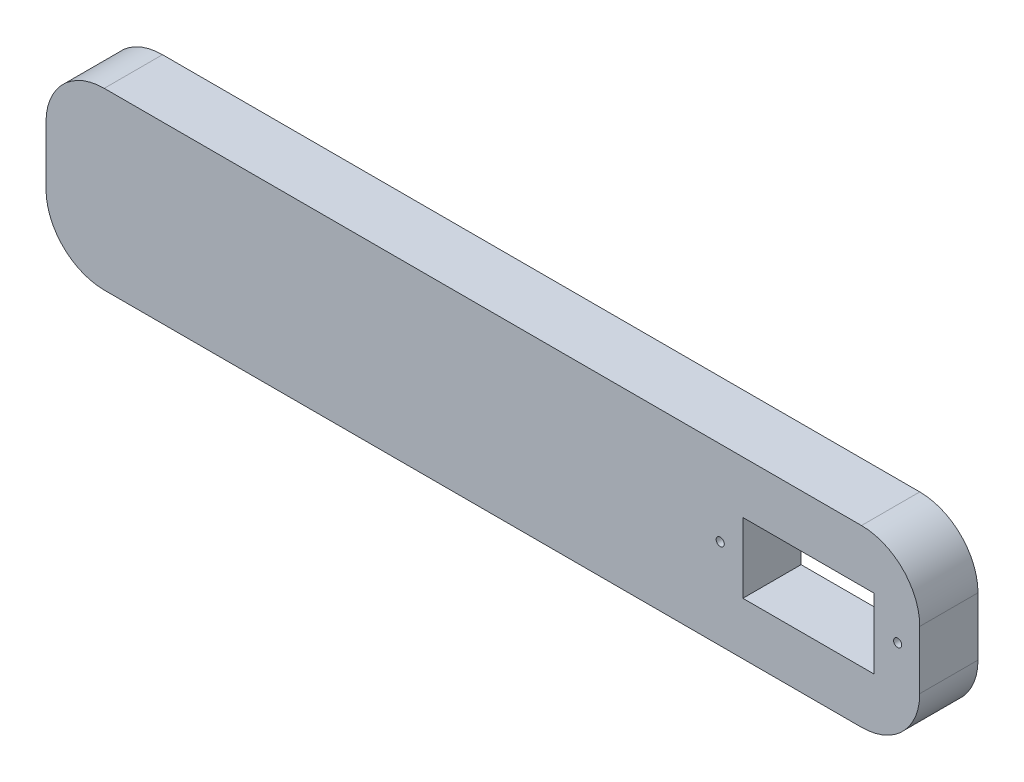
SolidWorks part; units mm, degrees
ref_plane "Front Plane" through (0, 0, 0) normal (0, 0, 1) x (1, 0, 0)
ref_plane "Top Plane" through (0, 0, 0) normal (0, 1, 0) x (1, 0, 0)
ref_plane "Right Plane" through (0, 0, 0) normal (1, 0, 0) x (0, 0, -1)
sketch "Sketch1" plane through (0, 0, 0) normal (0, 0, 1) x (1, 0, 0)
  line L1 (10, 0) -> (140, 0)
  line L2 (0, 10) -> (0, 20)
  line L3 (10, 30) -> (140, 30)
  line L4 (150, 10) -> (150, 20)
  arc A0 (0, 20) -> (10, 30) centre (10, 20) cw
  arc A1 (10, 0) -> (0, 10) centre (10, 10) cw
  arc A2 (140, 0) -> (150, 10) centre (140, 10) ccw
  arc A3 (140, 30) -> (150, 20) centre (140, 20) cw
  point P7 (0, 30)
  point P10 (0, 0)
  point P13 (150, 0)
  point P16 (150, 30)
  dimension "D3" = 10
  dimension "D4" = 10
  dimension "D5" = 10
  dimension "D1" = 150
  dimension "D2" = 30
extrude "Boss-Extrude1" add sketch "Sketch1" along normal blind 10 contours L2 A0 L3 A3 L4 A2 L1 A1
sketch "Sketch2" plane through (0, 0, 0) normal (0, 0, -1) x (-1, 0, 0)
  line L1 (-142.1527, 8.9966) -> (-119.6327, 8.9966)
  line L2 (-142.1527, 8.9966) -> (-142.1527, 21.0166)
  line L3 (-142.1527, 21.0166) -> (-119.6327, 21.0166)
  line L4 (-119.6327, 8.9966) -> (-119.6327, 21.0166)
  dimension "D1" = 12.02
  dimension "D2" = 22.52
extrude "Cut-Extrude1" cut sketch "Sketch2" against normal through all
sketch "Sketch3" plane through (0, 0, 0) normal (0, 0, -1) x (-1, 0, 0)
  circle A0 centre (-146.2094, 15.6684) radius 1.8868
  circle A1 centre (-115.744, 15.4538) radius 1.8868
  point P0 (-146.2094, 15.6684)
  point P6 (-115.744, 15.4538)
hole_wizard "CBORE for #00 Binding Head Machine Screw3" positions "Sketch3" profile "Sketch4" counterbore size "#00" standard "ANSI Inch" end condition through all
sketch "Sketch4" plane through (146.2094, 15.6684, 0) normal (1, 0, 0) x (0, 1, 0)
  line L0 (0, 0) -> (0, 10)
  line L1 (0, 10) -> (0.6985, 10)
  line L3 (0.6985, 10) -> (0.6985, 0.7112)
  line L4 (0.6985, 0.7112) -> (1.5875, 0.7112)
  line L5 (1.5875, 0.7112) -> (1.5875, 0)
  line L7 (1.5875, 0) -> (0, 0)
  line L11 (0, -6.35) -> (0, 107.95) construction
  dimension "Thru Hole Dia." = 1.397
  dimension "Thru Hole Depth" = 10
  dimension "C'Bore Dia." = 3.175
  dimension "C'Bore Depth" = 0.7112
